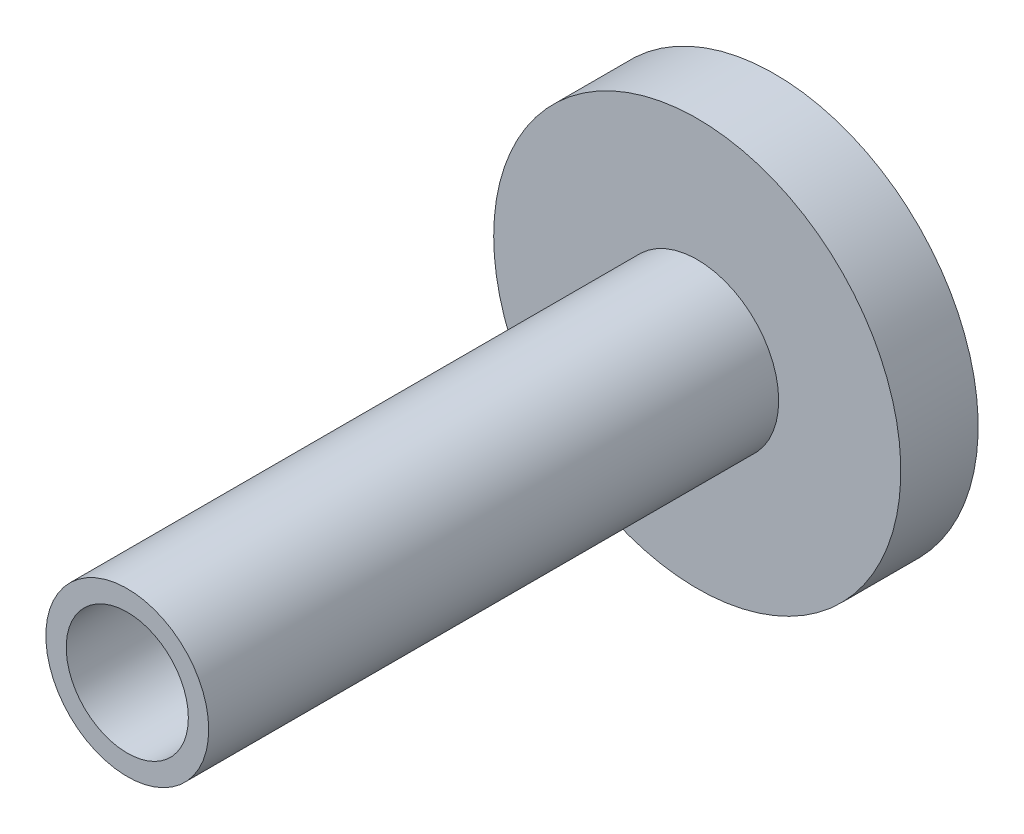
SolidWorks part; units mm, degrees
material "AISI 304"
ref_plane "前视基准面" through (0, 0, 0) normal (0, 0, 1) x (1, 0, 0)
ref_plane "上视基准面" through (0, 0, 0) normal (0, 1, 0) x (1, 0, 0)
ref_plane "右视基准面" through (0, 0, 0) normal (1, 0, 0) x (0, 0, -1)
sketch "草图1" plane through (0, 0, 0) normal (0, 0, 1) x (1, 0, 0)
  circle A0 centre (0, 0) radius 5
  dimension "D1" = 10
extrude "凸台-拉伸1" add sketch "草图1" along normal blind 1.9
sketch "草图2" plane through (0, 0, 1.9) normal (0, 0, 1) x (1, 0, 0)
  circle A0 centre (0, 0) radius 2
  dimension "D1" = 4
extrude "凸台-拉伸2" add sketch "草图2" along normal blind 14
sketch "草图3" plane through (0, 0, 15.9) normal (0, 0, 1) x (1, 0, 0)
  circle A0 centre (0, 0) radius 1.5
  dimension "D1" = 3
extrude "切除-拉伸1" cut sketch "草图3" against normal blind 12
cosmetic thread "装饰螺纹线1" parameters "D2"=3.6
